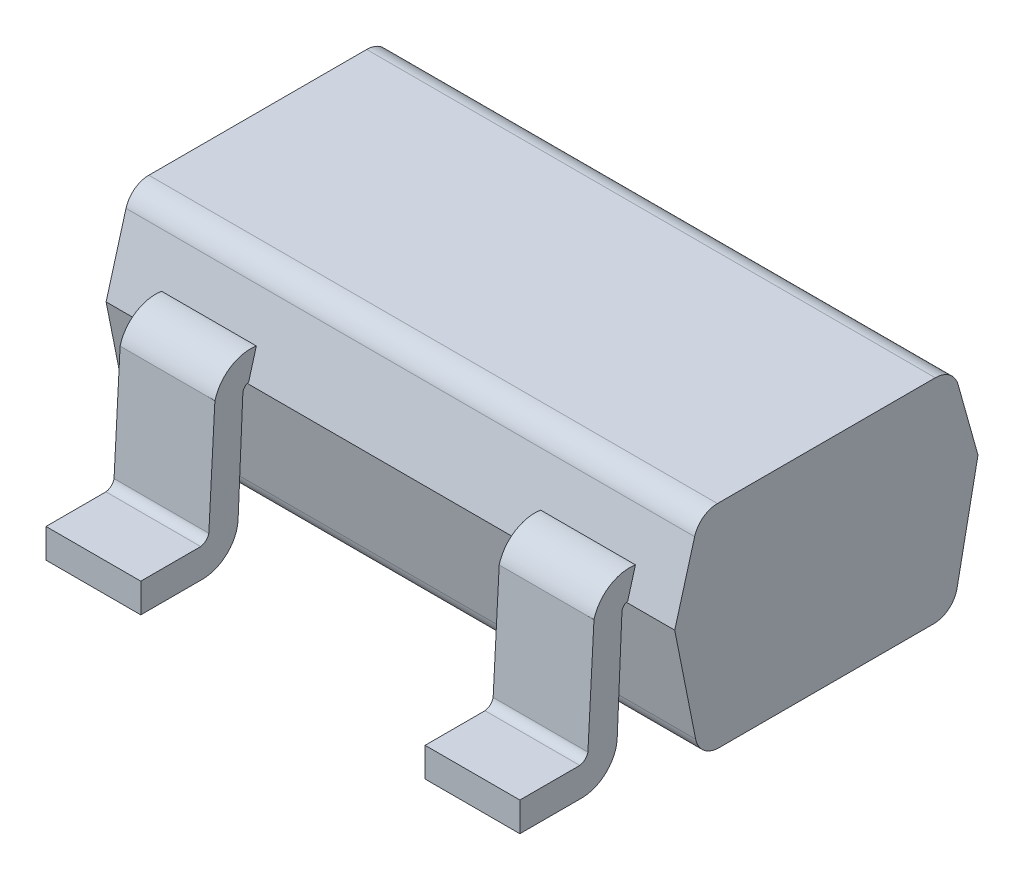
SolidWorks part; units mm, degrees
ref_plane "Front Plane" through (0, 0, 0) normal (0, 0, 1) x (1, 0, 0)
ref_plane "Top Plane" through (0, 0, 0) normal (0, 1, 0) x (1, 0, 0)
ref_plane "Right Plane" through (0, 0, 0) normal (1, 0, 0) x (0, 0, -1)
sketch "Sketch1" plane through (0, 0, 0) normal (0, 1, 0) x (1, 0, 0)
  line L1 (-1.5, -0.8) -> (1.5, -0.8)
  line L2 (-1.5, -0.8) -> (-1.5, 0.8)
  line L3 (-1.5, 0.8) -> (1.5, 0.8)
  line L4 (1.5, -0.8) -> (1.5, 0.8)
  line L5 (-1.5, -0.8) -> (1.5, 0.8) construction
  line L6 (-1.5, 0.8) -> (1.5, -0.8) construction
  point P0 (0, 0)
  dimension "D1" = 3
  dimension "D2" = 1.6
extrude "Boss-Extrude1" add sketch "Sketch1" along normal mid plane 1.12
sketch "Sketch3" plane through (1.5, 0, 0) normal (1, 0, 0) x (0, 0, -1)
  line L0 (-0.673, 0.3892) -> (0.927, 0.3892) construction
  line L1 (0, -1.104) -> (0, 1.104) construction
  line L2 (0, 0.56) -> (-0.5747, 0.56) construction
  line L3 (-0.8, 0.56) -> (0.8, 0.56) construction
  line L4 (-0.695, 0.4687) -> (-0.8, 0.094)
  line L5 (-0.8, 0.56) -> (-0.8, -0.56) construction
  line L6 (-0.8, 0.094) -> (-0.6895, -0.4595)
  line L7 (-0.8, -0.56) -> (0.8, -0.56) construction
  line L8 (-0.5669, -0.56) -> (0, -0.56) construction
  line L9 (-0.5747, 0.56) -> (-0.8, 0.56)
  line L10 (-0.8, 0.56) -> (-0.8, 0.094)
  line L11 (-0.5669, -0.56) -> (-0.8, -0.56)
  line L12 (-0.8, -0.56) -> (-0.8, 0.094)
  line L13 (0.8, -0.56) -> (0.8, 0.094)
  line L14 (0.5669, -0.56) -> (0.8, -0.56)
  line L15 (0.8, 0.56) -> (0.8, 0.094)
  line L16 (0.5747, 0.56) -> (0.8, 0.56)
  line L17 (0.8, 0.094) -> (0.6895, -0.4595)
  line L18 (0.695, 0.4687) -> (0.8, 0.094)
  arc A0 (-0.6895, -0.4595) -> (-0.5669, -0.56) centre (-0.5669, -0.435) ccw
  arc A1 (-0.5747, 0.56) -> (-0.695, 0.4687) centre (-0.5747, 0.435) ccw
  arc A2 (0.5747, 0.56) -> (0.695, 0.4687) centre (0.5747, 0.435) cw
  arc A3 (0.6895, -0.4595) -> (0.5669, -0.56) centre (0.5669, -0.435) cw
  point P7 (0, 0)
  point P19 (-0.6695, -0.56)
  point P22 (-0.6695, 0.56)
  point P36 (0.6695, 0.56)
  point P37 (0.6695, -0.56)
  line M5 (-0.8, -0.56) -> (0.8, -0.56)
  line M6 (0.8, -0.56) -> (0.8, 0.56)
  line M7 (0.8, 0.56) -> (-0.8, 0.56)
  line M8 (-0.8, 0.56) -> (-0.8, -0.56)
  dimension "D1" = 0.125
extrude "Cut-Extrude1" cut sketch "Sketch3" against normal through all contours A1 L4 M7 M8 | L17 A3 M5 M6 | A2 L18 M7 M6 | L6 A0 L11 L12
sketch "Sketch4" plane through (0, 0, 0) normal (1, 0, 0) x (0, 0, -1)
  line L0 (0.6832, 1.6039) -> (4.0394, 1.6039) construction
  line L1 (0.695, 0.4687) -> (0.8, 0.094) construction
  line L2 (0.976, 0.1052) -> (1.0081, -0.4843)
  line L3 (1.0508, -0.5235) -> (1.3671, -0.5235)
  line L4 (1.3671, -0.5235) -> (1.3671, -0.6777)
  line L5 (1.3671, -0.6777) -> (1.0508, -0.6777)
  line L6 (0.8529, -0.4843) -> (0.8283, 0.0704)
  line L7 (0.7978, 0.1019) -> (0.7573, 0.2463)
  arc A0 (0.7573, 0.2463) -> (0.976, 0.1052) centre (0.7885, 0.0546) cw
  arc A1 (1.0081, -0.4843) -> (1.0508, -0.5235) centre (1.0583, -0.4724) ccw
  arc A2 (0.8529, -0.4843) -> (1.0508, -0.6777) centre (1.043, -0.4877) ccw
  arc A3 (0.8283, 0.0704) -> (0.7978, 0.1019) centre (0.79, 0.0638) ccw
extrude "Boss-Extrude2" add sketch "Sketch4" along normal mid plane 0.5
sketch "Sketch5" plane through (0, 0, 0) normal (1, 0, 0) x (0, 0, -1)
  line L0 (0, 0) -> (0, 1.1119) construction
  line L1 (-1.0081, -0.4843) -> (-0.976, 0.1052)
  line L2 (-1.3671, -0.5235) -> (-1.0508, -0.5235)
  line L3 (-1.3671, -0.6777) -> (-1.3671, -0.5235)
  line L4 (-1.0508, -0.6777) -> (-1.3671, -0.6777)
  line L5 (-0.8283, 0.0704) -> (-0.8529, -0.4843)
  line L6 (0.7573, 0.2463) -> (0.7978, 0.1019)
  line L7 (0.8283, 0.0704) -> (0.8529, -0.4843)
  line L8 (1.0508, -0.6777) -> (1.3671, -0.6777)
  line L9 (1.3671, -0.6777) -> (1.3671, -0.5235)
  line L10 (1.3671, -0.5235) -> (1.0508, -0.5235)
  line L11 (1.0081, -0.4843) -> (0.976, 0.1052)
  line L12 (0.7573, 0.2463) -> (0.7978, 0.1019) construction
  line L13 (0.8283, 0.0704) -> (0.8529, -0.4843) construction
  line L14 (1.0508, -0.6777) -> (1.3671, -0.6777) construction
  line L15 (1.3671, -0.6777) -> (1.3671, -0.5235) construction
  line L16 (1.3671, -0.5235) -> (1.0508, -0.5235) construction
  line L17 (1.0081, -0.4843) -> (0.976, 0.1052) construction
  line L18 (-0.7573, 0.2463) -> (-0.7978, 0.1019)
  arc A0 (-1.0081, -0.4843) -> (-1.0508, -0.5235) centre (-1.0583, -0.4724) cw
  arc A1 (-0.8529, -0.4843) -> (-1.0508, -0.6777) centre (-1.043, -0.4877) cw
  arc A2 (-0.8283, 0.0704) -> (-0.7978, 0.1019) centre (-0.79, 0.0638) cw
  arc A3 (-0.976, 0.1052) -> (-0.7573, 0.2463) centre (-0.7885, 0.0546) cw
  arc A4 (0.976, 0.1052) -> (0.7573, 0.2463) centre (0.7885, 0.0546) ccw
  arc A5 (0.8283, 0.0704) -> (0.7978, 0.1019) centre (0.79, 0.0638) ccw
  arc A6 (0.8529, -0.4843) -> (1.0508, -0.6777) centre (1.043, -0.4877) ccw
  arc A7 (1.0081, -0.4843) -> (1.0508, -0.5235) centre (1.0583, -0.4724) ccw
  arc A8 (0.976, 0.1052) -> (0.7573, 0.2463) centre (0.7885, 0.0546) ccw construction
  arc A9 (0.8283, 0.0704) -> (0.7978, 0.1019) centre (0.79, 0.0638) ccw construction
  arc A10 (0.8529, -0.4843) -> (1.0508, -0.6777) centre (1.043, -0.4877) ccw construction
  arc A11 (1.0081, -0.4843) -> (1.0508, -0.5235) centre (1.0583, -0.4724) ccw construction
  dimension "D1" = 0
extrude "Boss-Extrude3" add sketch "Sketch5" along normal mid plane 0.5
pattern_linear "LPattern1" count 2 spacing 1 along (1, 0, 0) count 2 spacing 1 along (-1, 0, 0) of "Boss-Extrude3"
sketch "Sketch6" plane through (0.25, 0, 0) normal (1, 0, 0) x (0, 0, -1)
  line L6 (-1.0508, -0.5235) -> (-1.3671, -0.5235)
  line L7 (-1.3671, -0.5235) -> (-1.3671, -0.6777)
  line L8 (-1.3671, -0.6777) -> (-1.0508, -0.6777)
  line L9 (-0.8529, -0.4843) -> (-0.8283, 0.0704)
  line L10 (-0.7978, 0.1019) -> (-0.7573, 0.2463)
  line L11 (-0.976, 0.1052) -> (-1.0081, -0.4843)
  line L12 (-1.0508, -0.5235) -> (-1.3671, -0.5235)
  line L13 (-1.3671, -0.5235) -> (-1.3671, -0.6777)
  line L14 (-1.3671, -0.6777) -> (-1.0508, -0.6777)
  line L15 (-0.8529, -0.4843) -> (-0.8283, 0.0704)
  line L16 (-0.7978, 0.1019) -> (-0.7573, 0.2463)
  line L17 (-0.976, 0.1052) -> (-1.0081, -0.4843)
  arc A4 (-1.0508, -0.5235) -> (-1.0081, -0.4843) centre (-1.0583, -0.4724) ccw
  arc A5 (-1.0508, -0.6777) -> (-0.8529, -0.4843) centre (-1.043, -0.4877) ccw
  arc A6 (-0.7978, 0.1019) -> (-0.8283, 0.0704) centre (-0.79, 0.0638) ccw
  arc A7 (-0.7573, 0.2463) -> (-0.976, 0.1052) centre (-0.7885, 0.0546) ccw
  arc A8 (-1.0508, -0.5235) -> (-1.0081, -0.4843) centre (-1.0583, -0.4724) ccw
  arc A9 (-1.0508, -0.6777) -> (-0.8529, -0.4843) centre (-1.043, -0.4877) ccw
  arc A10 (-0.7978, 0.1019) -> (-0.8283, 0.0704) centre (-0.79, 0.0638) ccw
  arc A11 (-0.7573, 0.2463) -> (-0.976, 0.1052) centre (-0.7885, 0.0546) ccw
  dimension "D1" = 0
extrude "Cut-Extrude2" cut sketch "Sketch6" against normal blind 0.5
